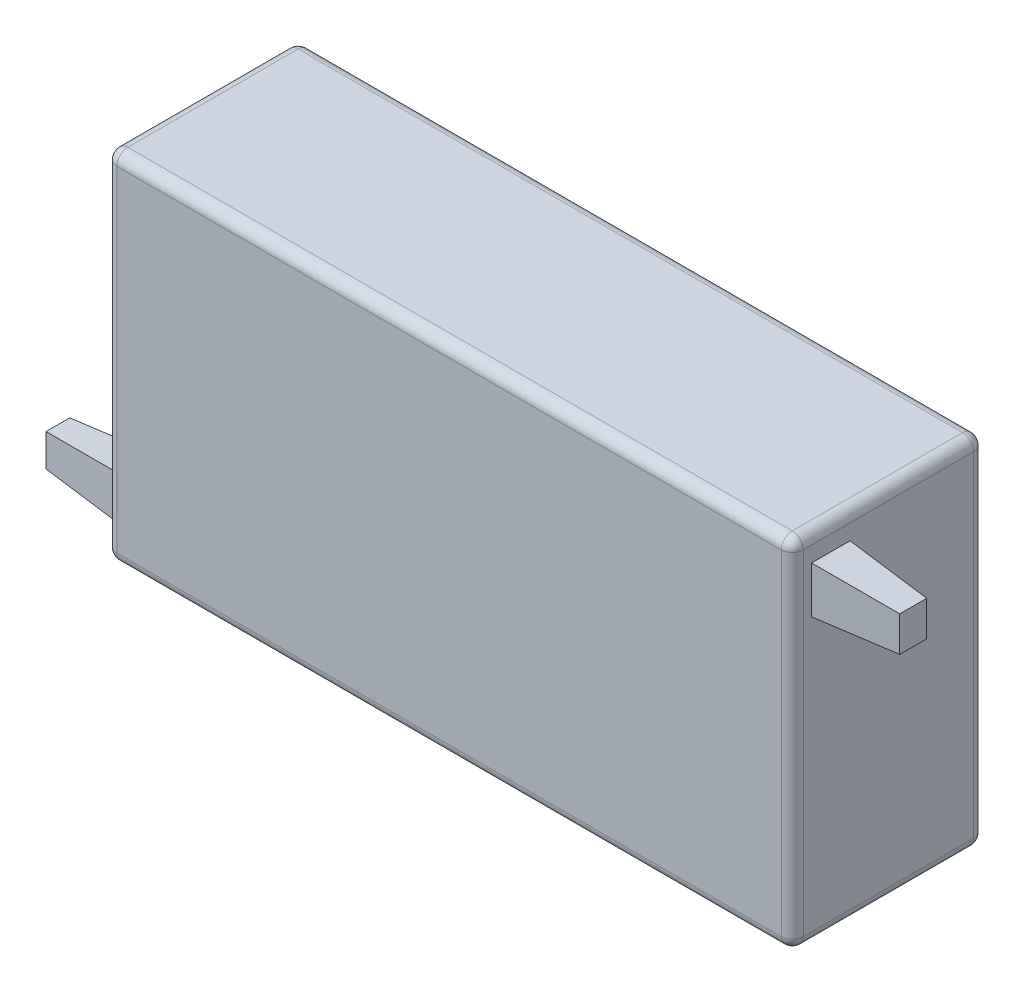
SolidWorks part; units mm, degrees
ref_plane "Front Plane" through (0, 0, 0) normal (0, 0, 1) x (1, 0, 0)
ref_plane "Top Plane" through (0, 0, 0) normal (0, 1, 0) x (1, 0, 0)
ref_plane "Right Plane" through (0, 0, 0) normal (1, 0, 0) x (0, 0, -1)
sketch "Sketch1" plane through (0, 0, 0) normal (0, 0, 1) x (1, 0, 0)
  line L1 (-62.5, 32.5) -> (62.5, 32.5)
  line L2 (-62.5, 32.5) -> (-62.5, -32.5)
  line L3 (-62.5, -32.5) -> (62.5, -32.5)
  line L4 (62.5, 32.5) -> (62.5, -32.5)
  line L5 (-62.5, 32.5) -> (62.5, -32.5) construction
  line L6 (-62.5, -32.5) -> (62.5, 32.5) construction
  point P0 (0, 0)
extrude "Boss-Extrude1" add sketch "Sketch1" along normal blind 35
fillet "Fillet1" radius 2 12 edges at (62.5, 0, 0) (0, -32.5, 0) (-62.5, 0, 0) (0, 32.5, 0) (-62.5, 32.5, 17.5) (-62.5, -32.5, 17.5) (62.5, 32.5, 17.5) (62.5, -32.5, 17.5) (0, 32.5, 35) (62.5, 0, 35) (0, -32.5, 35) (-62.5, 0, 35)
sketch "Sketch2" plane through (62.5, 0, 0) normal (1, 0, 0) x (0, 0, -1)
  line L1 (-31.4773, 27.6793) -> (-24.4773, 27.6793)
  line L2 (-31.4773, 27.6793) -> (-31.4773, 19.1793)
  line L3 (-31.4773, 19.1793) -> (-24.4773, 19.1793)
  line L4 (-24.4773, 27.6793) -> (-24.4773, 19.1793)
extrude "Boss-Extrude2" add sketch "Sketch2" along normal blind 15 draft 4
sketch "Sketch3" plane through (-62.5, 0, 0) normal (-1, 0, 0) x (0, 0, 1)
  line L1 (31.9577, -28.8316) -> (25.5318, -28.8316)
  line L2 (31.9577, -28.8316) -> (31.9577, -20.8283)
  line L3 (31.9577, -20.8283) -> (25.5318, -20.8283)
  line L4 (25.5318, -28.8316) -> (25.5318, -20.8283)
extrude "Boss-Extrude3" add sketch "Sketch3" along normal blind 15 draft 4
